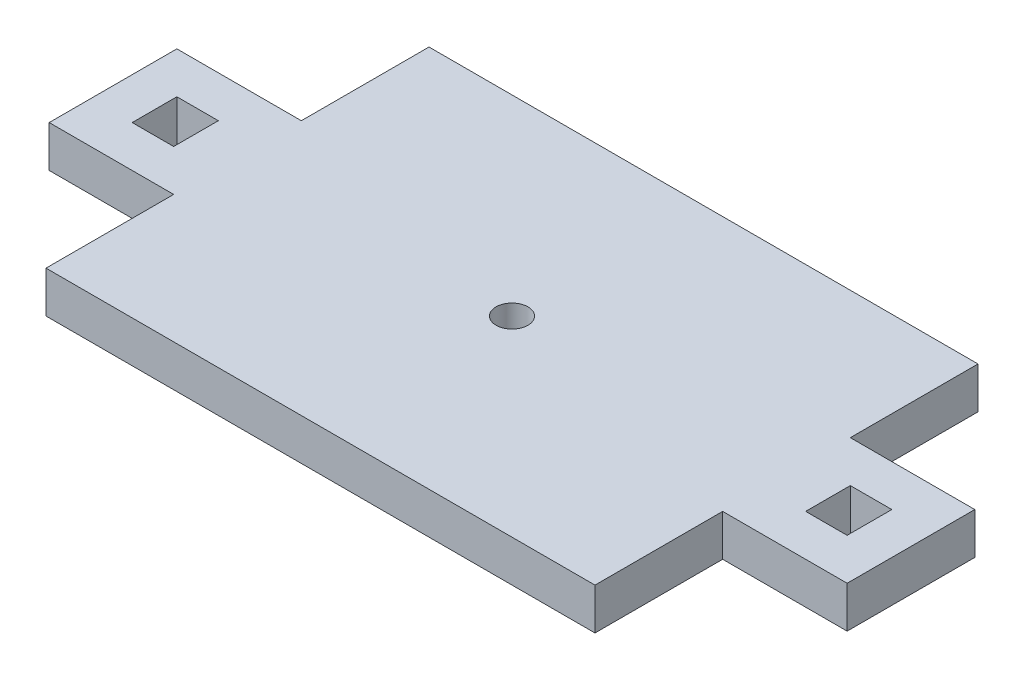
SolidWorks part; units mm, degrees
ref_plane "Front Plane" through (0, 0, 0) normal (0, 0, 1) x (1, 0, 0)
ref_plane "Top Plane" through (0, 0, 0) normal (0, 1, 0) x (1, 0, 0)
ref_plane "Right Plane" through (0, 0, 0) normal (1, 0, 0) x (0, 0, -1)
sketch "Sketch1" plane through (0, 0, 0) normal (0, 1, 0) x (1, 0, 0)
  line L1 (0, 0) -> (125, 0)
  line L2 (0, 0) -> (0, 60)
  line L3 (0, 60) -> (125, 60)
  line L4 (125, 0) -> (125, 60)
  dimension "D1" = 60
  dimension "D2" = 125
extrude "Boss-Extrude1" add sketch "Sketch1" along normal blind 6.5
sketch "Sketch2" plane through (0, 6.5, 0) normal (0, 1, 0) x (1, 0, 0)
  line L1 (0, 60) -> (19.5, 60)
  line L2 (0, 60) -> (0, 40)
  line L3 (0, 40) -> (19.5, 40)
  line L4 (19.5, 60) -> (19.5, 40)
  line L5 (0, 0) -> (19.5, 0)
  line L6 (0, 0) -> (0, 20)
  line L7 (0, 20) -> (19.5, 20)
  line L8 (19.5, 0) -> (19.5, 20)
  line L9 (125, 60) -> (105.5, 60)
  line L10 (125, 60) -> (125, 40)
  line L11 (125, 40) -> (105.5, 40)
  line L12 (105.5, 60) -> (105.5, 40)
  line L13 (125, 0) -> (105.5, 0)
  line L14 (125, 0) -> (125, 20)
  line L15 (125, 20) -> (105.5, 20)
  line L16 (105.5, 0) -> (105.5, 20)
  dimension "D1" = 20
  dimension "D2" = 19.5
extrude "Cut-Extrude1" cut sketch "Sketch2" against normal up to next
sketch "Sketch3" plane through (0, 6.5, 0) normal (0, 1, 0) x (1, 0, 0)
  line L0 (62.5, 30) -> (62.5, 60) construction
  line L1 (105.5, 60) -> (19.5, 60) construction
  line L2 (62.5, 30) -> (62.5, 0) construction
  line L3 (19.5, 0) -> (105.5, 0) construction
  line L4 (0, 30) -> (62.5, 30) construction
  line L5 (0, 40) -> (0, 20) construction
  line L6 (62.5, 30) -> (125, 30) construction
  line L7 (125, 20) -> (125, 40) construction
  circle A0 centre (62.5, 30) radius 2.5
  dimension "D1" = 5
extrude "Cut-Extrude2" cut sketch "Sketch3" against normal up to next
sketch "Sketch6" plane through (0, 6.5, 0) normal (0, 1, 0) x (1, 0, 0)
  line L0 (9.75, 33.5) -> (9.75, 40) construction
  line L1 (6.5, 33.5) -> (13, 33.5)
  line L2 (6.5, 33.5) -> (6.5, 26.5)
  line L3 (6.5, 26.5) -> (13, 26.5)
  line L4 (13, 33.5) -> (13, 26.5)
  line L5 (0, 40) -> (19.5, 40) construction
  line L6 (6.5, 30) -> (0, 30) construction
  line L7 (0, 40) -> (0, 20) construction
  line L8 (9.75, 26.5) -> (9.75, 20) construction
  line L9 (19.5, 20) -> (0, 20) construction
  line L10 (62.5, 60) -> (62.5, 0) construction
  line L11 (105.5, 60) -> (19.5, 60) construction
  line L12 (19.5, 0) -> (105.5, 0) construction
  line L13 (118.5, 26.5) -> (112, 26.5)
  line L14 (112, 33.5) -> (112, 26.5)
  line L15 (118.5, 33.5) -> (112, 33.5)
  line L16 (118.5, 33.5) -> (118.5, 26.5)
  dimension "D1" = 6.5
  dimension "D2" = 7
extrude "Cut-Extrude3" cut sketch "Sketch6" against normal up to next
